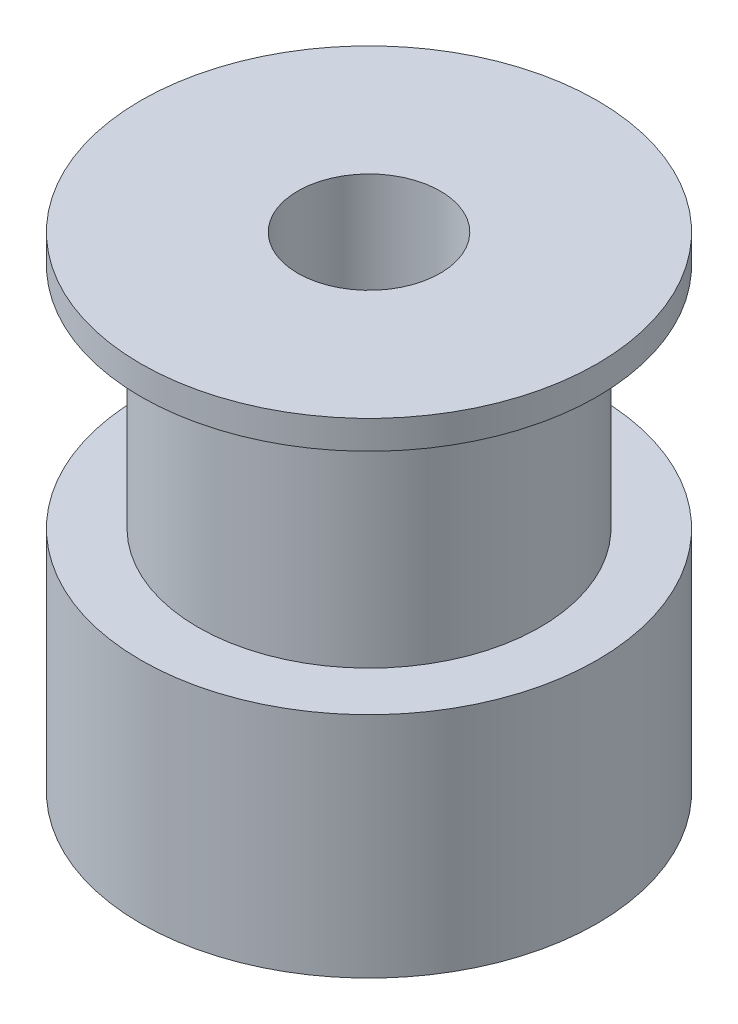
SolidWorks part; units mm, degrees
ref_plane "Front Plane" through (0, 0, 0) normal (0, 0, 1) x (1, 0, 0)
ref_plane "Top Plane" through (0, 0, 0) normal (0, 1, 0) x (1, 0, 0)
ref_plane "Right Plane" through (0, 0, 0) normal (1, 0, 0) x (0, 0, -1)
sketch "Sketch1" plane through (0, 0, 0) normal (0, 1, 0) x (1, 0, 0)
  circle A0 centre (0, 0) radius 8
  dimension "D1" = 16
extrude "Boss-Extrude1" add sketch "Sketch1" along normal blind 8
sketch "Sketch2" plane through (0, 8, 0) normal (0, 1, 0) x (1, 0, 0)
  circle A0 centre (0, 0) radius 6
  dimension "D1" = 12
extrude "Boss-Extrude2" add sketch "Sketch2" along normal blind 8
sketch "Sketch3" plane through (0, 16, 0) normal (0, 1, 0) x (1, 0, 0)
  circle A0 centre (0, 0) radius 8
  dimension "D1" = 16
extrude "Boss-Extrude3" add sketch "Sketch3" along normal blind 1
sketch "Sketch4" plane through (0, 17, 0) normal (0, 1, 0) x (1, 0, 0)
  circle A0 centre (0, 0) radius 2.5
  dimension "D1" = 5
extrude "Cut-Extrude1" cut sketch "Sketch4" against normal through all
